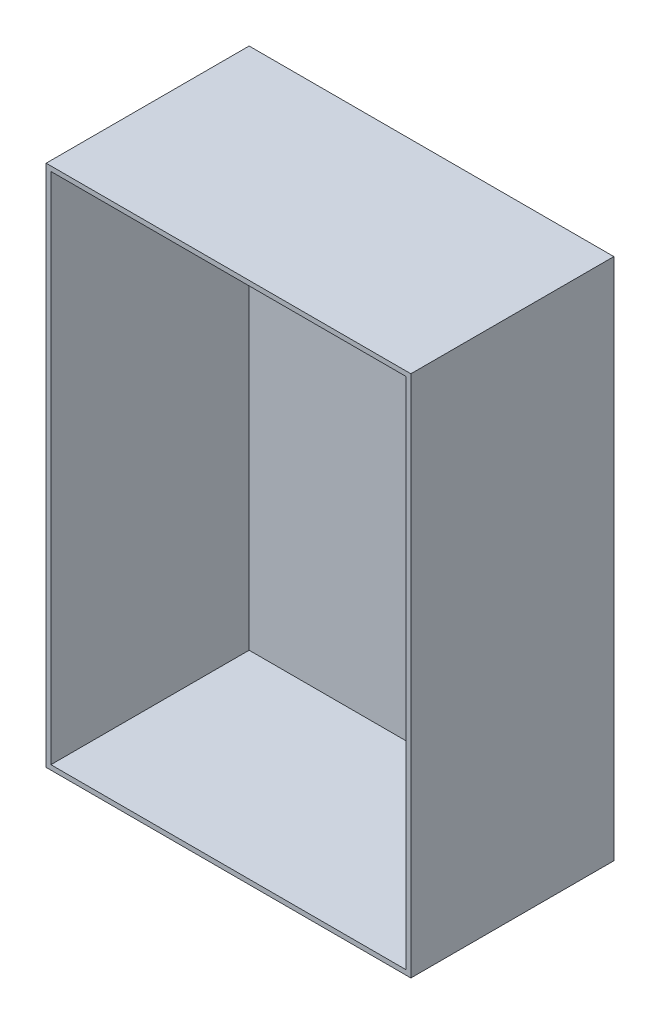
SolidWorks part; units mm, degrees
ref_plane "Front Plane" through (0, 0, 0) normal (0, 0, 1) x (1, 0, 0)
ref_plane "Top Plane" through (0, 0, 0) normal (0, 1, 0) x (1, 0, 0)
ref_plane "Right Plane" through (0, 0, 0) normal (1, 0, 0) x (0, 0, -1)
sketch "Sketch1" plane through (0, 0, 0) normal (0, 0, 1) x (1, 0, 0)
  line L1 (0, 0) -> (230, 0)
  line L2 (0, 0) -> (0, 330)
  line L3 (0, 330) -> (230, 330)
  line L4 (230, 0) -> (230, 330)
  line L6 (3, 3) -> (227, 3)
  line L7 (3, 3) -> (3, 327)
  line L8 (3, 327) -> (227, 327)
  line L9 (227, 3) -> (227, 327)
  dimension "D1" = 3
  dimension "D2" = 227
  dimension "D3" = 230
  dimension "D4" = 3
  dimension "D5" = 327
  dimension "D6" = 330
extrude "Profile" add sketch "Sketch1" along normal blind 128
sketch "Sketch2" plane through (0, 0, 0) normal (0, 0, 1) x (1, 0, 0)
  line L1 (3, 3) -> (227, 3)
  line L2 (3, 3) -> (3, 327)
  line L3 (3, 327) -> (227, 327)
  line L4 (227, 3) -> (227, 327)
  dimension "D1" = 224
  dimension "D2" = 324
extrude "Back" add sketch "Sketch2" along normal blind 3
equation "\"Profile_Depth\" = 128mm"
equation "\"D1@Profile\" = \"Profile_Depth\""
equation "\"Profile_Sketch_1\" = 3mm"
equation "\"D1@Sketch1\" = \"Profile_Sketch_1\""
equation "\"Profile_Sketch_2\" = 227mm"
equation "\"D2@Sketch1\" = \"Profile_Sketch_2\""
equation "\"Profile_Sketch_3\" = 230mm"
equation "\"D3@Sketch1\" = \"Profile_Sketch_3\""
equation "\"Profile_Sketch_4\" = 3mm"
equation "\"D4@Sketch1\" = \"Profile_Sketch_4\""
equation "\"Profile_Sketch_5\" = 327mm"
equation "\"D5@Sketch1\" = \"Profile_Sketch_5\""
equation "\"Profile_Sketch_6\" = 330mm"
equation "\"D6@Sketch1\" = \"Profile_Sketch_6\""
equation "\"Back_Depth\" = 3mm"
equation "\"D1@Back\" = \"Back_Depth\""
equation "\"Back_Sketch_1\" = 224mm"
equation "\"D1@Sketch2\" = \"Back_Sketch_1\""
equation "\"Back_Sketch_2\" = 324mm"
equation "\"D2@Sketch2\" = \"Back_Sketch_2\""
equation "\"EnvelopeWidth\" = 230mm"
equation "\"EnvelopeHeight\" = 330mm"
